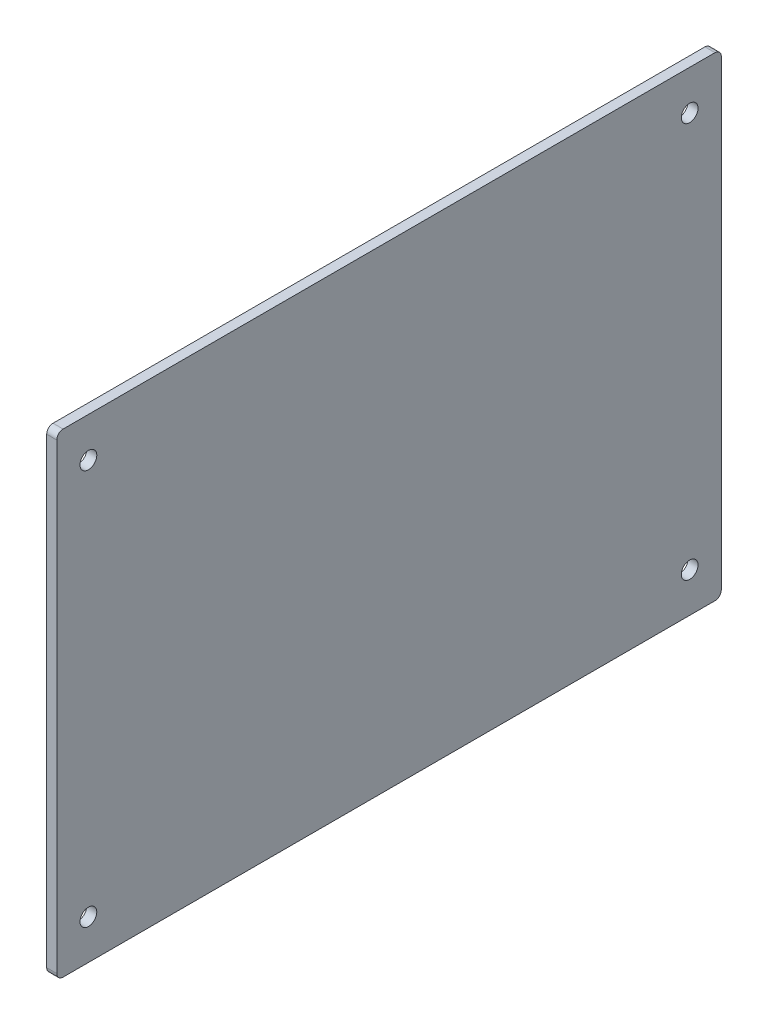
SolidWorks part; units mm, degrees
material "6061 Alloy"
ref_plane "Front Plane" through (0, 0, 0) normal (0, 0, 1) x (1, 0, 0)
ref_plane "Top Plane" through (0, 0, 0) normal (0, 1, 0) x (1, 0, 0)
ref_plane "Right Plane" through (0, 0, 0) normal (1, 0, 0) x (0, 0, -1)
sketch "Sketch2" plane through (0, 0, 0) normal (1, 0, 0) x (0, 0, -1)
  line L1 (-105, -75) -> (105, -75)
  line L2 (-105, -75) -> (-105, 75)
  line L3 (-105, 75) -> (105, 75)
  line L4 (105, -75) -> (105, 75)
  line L5 (-105, -75) -> (105, 75) construction
  line L6 (-105, 75) -> (105, -75) construction
  line L7 (95, -62.5) -> (-95, -62.5) construction
  line L8 (95, -62.5) -> (95, 62.5) construction
  line L9 (95, 62.5) -> (-95, 62.5) construction
  line L10 (-95, -62.5) -> (-95, 62.5) construction
  line L11 (95, -62.5) -> (-95, 62.5) construction
  line L12 (95, 62.5) -> (-95, -62.5) construction
  point P0 (0, 0)
  point P6 (0, 0)
  dimension "D1" = 150
  dimension "D2" = 210
  dimension "D3" = 190
  dimension "D4" = 125
extrude "Boss-Extrude1" add sketch "Sketch2" along normal blind 3.175
hole_wizard "M5 Clearance Hole1" [suppressed] positions "Sketch3" profile "Sketch4" hole size "M5" standard "ANSI Metric"
sketch "Sketch3" [suppressed] plane through (3.175, 0, 0) normal (1, 0, 0) x (0, 0, -1)
  point P0 (-62.5, 125)
  point P3 (62.5, 125)
  point P6 (-62.5, -125)
  point P9 (62.5, -125)
sketch "Sketch4" plane through (3.175, 125, 62.5) normal (0, 1, 0) x (0, 0, -1)
  line L0 (0, 0) -> (0, 3.175)
  line L1 (0, 3.175) -> (2.65, 3.175)
  line L2 (2.65, 3.175) -> (2.65, 0)
  line L5 (2.65, 0) -> (0, 0)
  line L11 (0, -6.35) -> (0, 107.95) construction
  dimension "Thru Hole Dia." = 5.3
  dimension "Thru Hole Depth" = 3.175
fillet "Fillet1" [suppressed] radius 2
hole_wizard "M5 Clearance Hole2" positions "Sketch5" profile "Sketch6" hole size "M5" standard "ANSI Metric" end condition through all
sketch "Sketch5" plane through (3.175, 0, 0) normal (1, 0, 0) x (0, 0, -1)
  point P0 (-95, 62.5)
  point P3 (95, 62.5)
  point P6 (-95, -62.5)
  point P9 (95, -62.5)
sketch "Sketch6" plane through (3.175, 62.5, 95) normal (0, 1, 0) x (0, 0, -1)
  line L0 (0, 0) -> (0, 3.175)
  line L1 (0, 3.175) -> (2.65, 3.175)
  line L2 (2.65, 3.175) -> (2.65, 0)
  line L5 (2.65, 0) -> (0, 0)
  line L11 (0, -6.35) -> (0, 107.95) construction
  dimension "Thru Hole Dia." = 5.3
  dimension "Thru Hole Depth" = 3.175
hole_wizard "M5 Clearance Hole3" [suppressed] positions "Sketch7" profile "Sketch8" hole size "M5" standard "ANSI Metric"
sketch "Sketch7" [suppressed] plane through (3.175, 0, 0) normal (1, 0, 0) x (0, 0, -1)
  point P0 (-95, 125)
  point P3 (95, 125)
  point P6 (-95, -125)
  point P9 (95, -125)
sketch "Sketch8" plane through (3.175, 125, 95) normal (0, 1, 0) x (0, 0, -1)
  line L0 (0, 0) -> (0, 3.175)
  line L1 (0, 3.175) -> (2.65, 3.175)
  line L2 (2.65, 3.175) -> (2.65, 0)
  line L5 (2.65, 0) -> (0, 0)
  line L11 (0, -6.35) -> (0, 107.95) construction
  dimension "Thru Hole Dia." = 5.3
  dimension "Thru Hole Depth" = 3.175
sketch "Sketch9" [suppressed] plane through (3.175, 0, 0) normal (1, 0, 0) x (0, 0, -1)
  line L0 (105, -150) -> (105, 150) construction
  line L1 (-105, -75) -> (105, -75)
  line L2 (-105, -75) -> (-105, 75)
  line L3 (-105, 75) -> (105, 75)
  line L4 (105, -75) -> (105, 75)
  line L5 (-105, -75) -> (105, 75) construction
  line L6 (-105, 75) -> (105, -75) construction
  point P0 (0, 0)
  dimension "D1" = 150
fillet "Fillet2" radius 2 4 edges at (1.5875, -75, -105) (1.5875, -75, 105) (1.5875, 75, -105) (1.5875, 75, 105)
